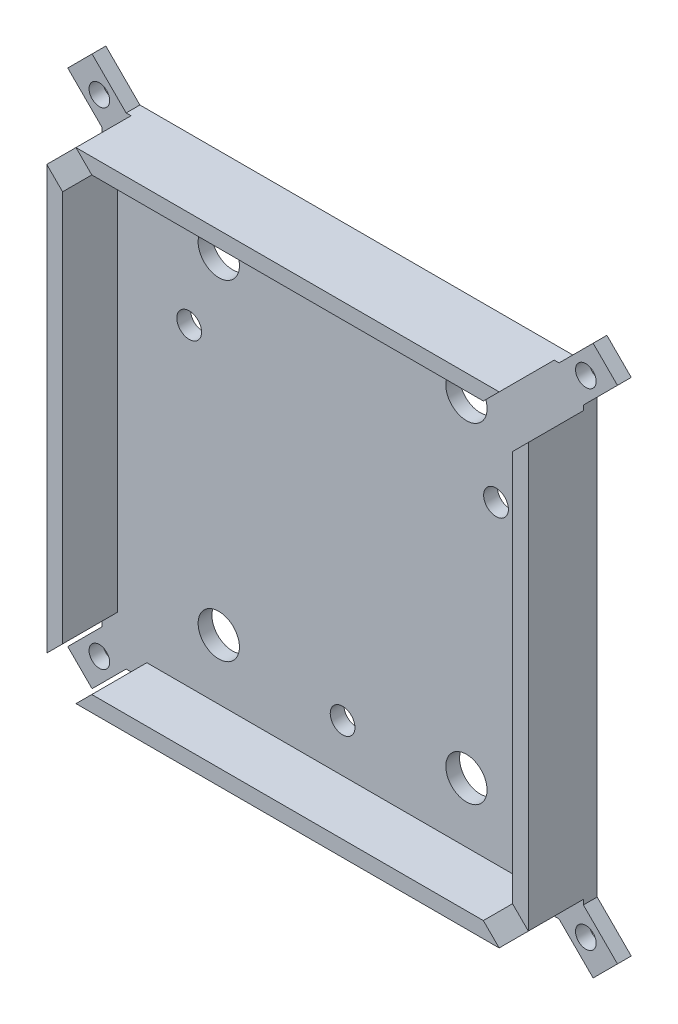
SolidWorks part; units mm, degrees
ref_plane "前视基准面" through (0, 0, 0) normal (0, 0, 1) x (1, 0, 0)
ref_plane "上视基准面" through (0, 0, 0) normal (0, 1, 0) x (1, 0, 0)
ref_plane "右视基准面" through (0, 0, 0) normal (1, 0, 0) x (0, 0, -1)
other "Configuration Table"
sketch "草图1" plane through (0, 0, 0) normal (0, 0, 1) x (1, 0, 0)
  line L1 (-33, -35) -> (33, -35)
  line L2 (-35, -33) -> (-35, 33)
  line L3 (-33, 35) -> (33, 35)
  line L4 (35, -33) -> (35, 33)
  line L5 (-35, -35) -> (35, 35) construction
  line L6 (-35, 35) -> (35, -35) construction
  arc A2 (-33, -35) -> (-35, -33) centre (-33, -33) cw
  arc A3 (33, -35) -> (35, -33) centre (33, -33) ccw
  arc A4 (35, 33) -> (33, 35) centre (33, 33) ccw
  arc A5 (-35, 33) -> (-33, 35) centre (-33, 33) cw
  point P0 (0, 0)
  dimension "D1" = 70
  dimension "D2" = 70
  dimension "D3" = 2
extrude "凸台-拉伸1" add sketch "草图1" along normal blind 10 contours A5 L2 A2 L1 A3 L4 A4 L3
sketch "草图2" plane through (0, 0, 10) normal (0, 0, 1) x (1, 0, 0)
  line L0 (-24, 18) -> (24, 18) construction
  line L1 (24, 18) -> (24, -18) construction
  line L2 (24, -18) -> (-24, -18) construction
  line L3 (-24, -18) -> (-24, 18) construction
  line L4 (-24, 18) -> (24, -18) construction
  line L5 (24, 18) -> (-24, -18) construction
  line L6 (-29.7, -32.7) -> (29.7, -32.7)
  line L7 (-32.7, -29.7) -> (-32.7, 29.7)
  line L8 (-29.7, 32.7) -> (29.7, 32.7)
  line L9 (32.7, -29.7) -> (32.7, 29.7)
  line L10 (-32.7, -32.7) -> (32.7, 32.7) construction
  line L11 (-32.7, 32.7) -> (32.7, -32.7) construction
  circle A0 centre (24, 18) radius 1.8
  circle A1 centre (-24, 18) radius 1.8
  circle A2 centre (-24, -18) radius 1.8
  circle A3 centre (24, -18) radius 1.8
  arc A4 (-32.7, 29.7) -> (-29.7, 32.7) centre (-29.7, 29.7) cw
  arc A5 (-32.7, -29.7) -> (-29.7, -32.7) centre (-29.7, -29.7) ccw
  arc A6 (29.7, -32.7) -> (32.7, -29.7) centre (29.7, -29.7) ccw
  arc A7 (32.7, 29.7) -> (29.7, 32.7) centre (29.7, 29.7) ccw
  point P8 (0, 0)
  point P9 (0, 0)
  dimension "D3" = 3.6
  dimension "D4" = 3.6
  dimension "D5" = 3.6
  dimension "D6" = 3.6
  dimension "D8" = 3
  dimension "D9" = 3
  dimension "D1" = 48
  dimension "D2" = 36
  dimension "D7" = 65.4
extrude "切除-拉伸1" cut sketch "草图2" against normal offset from surface (8 mm away) 2 contours L8 A7 L9 A6 L6 A5 L7 A4 up to face at (0, 0, 0)
sketch "草图3" plane through (0, 0, 0) normal (0, 0, -1) x (-1, 0, 0)
  line L0 (-14.4627, 17.236) -> (-18.6408, 22.2153)
  line L1 (-28.5594, 5.0358) -> (-22.1582, 3.9071)
  line L2 (-25.1147, 14.5) -> (-19.4856, 11.25)
  line L3 (0, 0) -> (50000, 0) construction
  line L4 (0, 0) -> (0, 50000) construction
  line L5 (22.1582, 3.9071) -> (28.5594, 5.0358)
  line L6 (18.6408, 22.2153) -> (14.4627, 17.236)
  line L7 (-7.6955, -21.1431) -> (-9.9186, -27.2511)
  line L8 (9.9186, -27.2511) -> (7.6955, -21.1431)
  arc A0 (-18.6408, 22.2153) -> (-28.5594, 5.0358) centre (0, 0) ccw
  arc A1 (-14.4627, 17.236) -> (-22.1582, 3.9071) centre (0, 0) ccw
  circle A2 centre (0, 0) radius 22.5 construction
  circle A3 centre (0, 0) radius 29 construction
  arc A4 (22.1582, 3.9071) -> (14.4627, 17.236) centre (0, 0) ccw
  arc A5 (28.5594, 5.0358) -> (18.6408, 22.2153) centre (0, 0) ccw
  arc A6 (-7.6955, -21.1431) -> (7.6955, -21.1431) centre (0, 0) ccw
  arc A7 (-9.9186, -27.2511) -> (9.9186, -27.2511) centre (0, 0) ccw
  circle A8 centre (-22.3002, 12.875) radius 1.8
  circle A9 centre (22.3002, 12.875) radius 1.8
  circle A10 centre (0, -25.75) radius 1.8
  point P9 (-22.3002, 12.875)
  point P25 (0, 0)
  point P32 (0, 0)
  dimension "D1" = 45
  dimension "D2" = 58
  dimension "D6" = 3.6
  dimension "D3" = 25.75
  dimension "D4" = 20
  dimension "D5" = 30
extrude "切除-拉伸2" cut sketch "草图3" against normal up to next contours A8 | A9 | A10
sketch "草图4" plane through (0, 0, 0) normal (0, 0, -1) x (-1, 0, 0)
  line L0 (-18, 24) -> (18, 24) construction
  line L1 (18, 24) -> (18, -24) construction
  line L2 (18, -24) -> (-18, -24) construction
  line L3 (-18, -24) -> (-18, 24) construction
  line L4 (-18, 24) -> (18, -24) construction
  line L5 (18, 24) -> (-18, -24) construction
  line L6 (-32.7, -32.7) -> (32.7, -32.7)
  line L7 (-32.7, -32.7) -> (-32.7, 32.7)
  line L8 (-32.7, 32.7) -> (32.7, 32.7)
  line L9 (32.7, -32.7) -> (32.7, 32.7)
  line L10 (-32.7, -32.7) -> (32.7, 32.7) construction
  line L11 (-32.7, 32.7) -> (32.7, -32.7) construction
  circle A0 centre (18, 24) radius 3
  circle A1 centre (-18, 24) radius 3
  circle A2 centre (-18, -24) radius 3
  circle A3 centre (18, -24) radius 3
  point P8 (0, 0)
  point P9 (0, 0)
  dimension "D3" = 6
  dimension "D4" = 6
  dimension "D5" = 6
  dimension "D6" = 6
  dimension "D1" = 36
  dimension "D2" = 48
  dimension "D7" = 65.4
extrude "切除-拉伸3" cut sketch "草图4" against normal through all contours A1 | A0 | A2 | A3
sketch "草图5" plane through (0, 0, 10) normal (0, 0, 1) x (1, 0, 0)
  line L0 (0, 0) -> (-34.4142, 34.4142) construction
  line L1 (-36.182, 32.6464) -> (-32.6464, 36.182) construction
  line L4 (33, 35) -> (-33, 35)
  line L5 (-35, 33) -> (-35, -33)
  line L6 (-33, -35) -> (33, -35)
  line L7 (35, -33) -> (35, 33)
  line L8 (33, 35) -> (-33, 35)
  line L9 (-35, 33) -> (-35, -33)
  line L10 (-33, -35) -> (33, -35)
  line L11 (35, -33) -> (35, 33)
  line L12 (-36.182, 32.6464) -> (-39.9515, 36.416)
  line L13 (-32.6464, 36.182) -> (-36.416, 39.9515)
  line L14 (-39.9515, 36.416) -> (-36.416, 39.9515)
  line L15 (-36.182, 32.6464) -> (-32.6464, 36.182) construction
  line L16 (-36.182, 32.6464) -> (-32.1734, 28.6378)
  line L17 (-32.6464, 36.182) -> (-28.6378, 32.1734)
  line L18 (-32.1734, 28.6378) -> (-28.6378, 32.1734)
  line L19 (32.6464, 36.182) -> (36.416, 39.9515)
  line L20 (36.182, 32.6464) -> (39.9515, 36.416)
  line L21 (36.416, 39.9515) -> (39.9515, 36.416)
  line L22 (32.6464, 36.182) -> (28.6378, 32.1734)
  line L23 (36.182, 32.6464) -> (32.1734, 28.6378)
  line L24 (28.6378, 32.1734) -> (32.1734, 28.6378)
  line L25 (32.6464, 36.182) -> (36.182, 32.6464) construction
  line L26 (32.6464, 36.182) -> (36.182, 32.6464) construction
  line L27 (36.182, -32.6464) -> (39.9515, -36.416)
  line L28 (32.6464, -36.182) -> (36.416, -39.9515)
  line L29 (39.9515, -36.416) -> (36.416, -39.9515)
  line L30 (36.182, -32.6464) -> (32.1734, -28.6378)
  line L31 (32.6464, -36.182) -> (28.6378, -32.1734)
  line L32 (32.1734, -28.6378) -> (28.6378, -32.1734)
  line L33 (36.182, -32.6464) -> (32.6464, -36.182) construction
  line L34 (36.182, -32.6464) -> (32.6464, -36.182) construction
  line L35 (-32.6464, -36.182) -> (-36.416, -39.9515)
  line L36 (-36.182, -32.6464) -> (-39.9515, -36.416)
  line L37 (-36.416, -39.9515) -> (-39.9515, -36.416)
  line L38 (-32.6464, -36.182) -> (-28.6378, -32.1734)
  line L39 (-36.182, -32.6464) -> (-32.1734, -28.6378)
  line L40 (-28.6378, -32.1734) -> (-32.1734, -28.6378)
  line L41 (-32.6464, -36.182) -> (-36.182, -32.6464) construction
  line L42 (-32.6464, -36.182) -> (-36.182, -32.6464) construction
  arc A0 (35, 33) -> (33, 35) centre (33, 33) ccw
  arc A1 (33, -35) -> (35, -33) centre (33, -33) ccw
  arc A2 (-35, -33) -> (-33, -35) centre (-33, -33) ccw
  arc A4 (-33, 35) -> (-35, 33) centre (-33, 33) ccw
  arc A5 (-35, -33) -> (-33, -35) centre (-33, -33) ccw
  arc A6 (33, -35) -> (35, -33) centre (33, -33) ccw
  arc A7 (35, 33) -> (33, 35) centre (33, 33) ccw
  arc A8 (-33, 35) -> (-35, 33) centre (-33, 33) ccw
  arc A9 (-35, -33) -> (-33, -35) centre (-33, -33) ccw
  arc A10 (33, -35) -> (35, -33) centre (33, -33) ccw
  arc A11 (35, 33) -> (33, 35) centre (33, 33) ccw
  point P12 (-34.4142, 34.4142)
  point P52 (0, 0)
  arc M21 (-29.7, -32.7) -> (-32.7, -29.7) centre (-29.7, -29.7) cw
  line M22 (-32.7, -29.7) -> (-32.7, 29.7)
  arc M23 (-32.7, 29.7) -> (-29.7, 32.7) centre (-29.7, 29.7) cw
  line M24 (-29.7, 32.7) -> (29.7, 32.7)
  arc M25 (29.7, 32.7) -> (32.7, 29.7) centre (29.7, 29.7) cw
  line M26 (32.7, 29.7) -> (32.7, -29.7)
  arc M27 (32.7, -29.7) -> (29.7, -32.7) centre (29.7, -29.7) cw
  line M28 (29.7, -32.7) -> (-29.7, -32.7)
  line M29 (33, 35) -> (-33, 35)
  arc M30 (-33, 35) -> (-35, 33) centre (-33, 33) ccw
  line M31 (-35, 33) -> (-35, -33)
  arc M32 (-35, -33) -> (-33, -35) centre (-33, -33) ccw
  line M33 (-33, -35) -> (33, -35)
  arc M34 (33, -35) -> (35, -33) centre (33, -33) ccw
  line M35 (35, -33) -> (35, 33)
  arc M36 (35, 33) -> (33, 35) centre (33, 33) ccw
  dimension "D2" = 4
  dimension "D3" = 5
  dimension "D4" = 43
  dimension "D5" = 54
  dimension "D1" = 0
extrude "凸台-拉伸2" add sketch "草图5" against normal up to surface (10 mm away) contours L17 L8 L16 M30 M31 M22 M23 M24 | L17 L13 L14 L12 L16 L8 M31 M30 | L23 L11 L22 M36 M29 M24 M25 M26 | L23 L20 L21 L19 L22 L11 M29 M36 | L31 L28 L29 L27 L30 L10 M35 M34 | L31 L10 L30 M34 M35 M26 M27 M28 | L39 L36 L37 L35 L38 M33 M32 M31 | L39 L38 M31 M32 M33 M28 M21 M22 up to face at (-21, 24, 0)
sketch "草图6" plane through (0, 0, 10) normal (0, 0, 1) x (1, 0, 0)
  line L0 (32.5, -32.5) -> (32.5, 32.5) construction
  line L1 (32.5, 32.5) -> (-32.5, 32.5) construction
  line L2 (-32.5, -32.5) -> (32.5, -32.5) construction
  line L3 (0, 0) -> (-38.1838, 38.1838) construction
  line L13 (-28.2574, -32.5) -> (28.2574, -32.5)
  line L16 (-36.416, -39.9515) -> (-31.4645, -35)
  line L17 (-31.4645, -35) -> (31.4645, -35)
  line L18 (31.4645, -35) -> (36.416, -39.9515)
  line L19 (36.416, -39.9515) -> (39.9515, -36.416)
  line L20 (39.9515, -36.416) -> (35, -31.4645)
  line L21 (35, -31.4645) -> (35, 31.4645)
  line L22 (35, 31.4645) -> (39.9515, 36.416)
  line L23 (39.9515, 36.416) -> (36.416, 39.9515)
  line L24 (36.416, 39.9515) -> (31.4645, 35)
  line L25 (31.4645, 35) -> (-31.4645, 35)
  line L26 (-31.4645, 35) -> (-36.416, 39.9515)
  line L27 (-36.416, 39.9515) -> (-39.9515, 36.416)
  line L28 (-39.9515, 36.416) -> (-35, 31.4645)
  line L29 (-35, 31.4645) -> (-35, -31.4645)
  line L30 (-35, -31.4645) -> (-39.9515, -36.416)
  line L31 (-39.9515, -36.416) -> (-36.416, -39.9515)
  line L32 (-36.416, -39.9515) -> (-31.4645, -35)
  line L33 (-31.4645, -35) -> (31.4645, -35)
  line L34 (31.4645, -35) -> (36.416, -39.9515)
  line L35 (36.416, -39.9515) -> (39.9515, -36.416)
  line L36 (39.9515, -36.416) -> (35, -31.4645)
  line L37 (35, -31.4645) -> (35, 31.4645)
  line L38 (35, 31.4645) -> (39.9515, 36.416)
  line L39 (39.9515, 36.416) -> (36.416, 39.9515)
  line L40 (36.416, 39.9515) -> (31.4645, 35)
  line L41 (31.4645, 35) -> (-31.4645, 35)
  line L42 (-31.4645, 35) -> (-36.416, 39.9515)
  line L43 (-36.416, 39.9515) -> (-39.9515, 36.416)
  line L44 (-39.9515, 36.416) -> (-35, 31.4645)
  line L45 (-35, 31.4645) -> (-35, -31.4645)
  line L46 (-35, -31.4645) -> (-39.9515, -36.416)
  line L47 (-39.9515, -36.416) -> (-36.416, -39.9515)
  line L49 (32.5, -28.2574) -> (32.5, 28.2574)
  line L53 (28.2574, 32.5) -> (-28.2574, 32.5)
  line L57 (-32.5, 28.2574) -> (-32.5, -28.2574)
  line L61 (-35, 30.7574) -> (-31.8859, 27.6432)
  line L62 (-31.8859, 27.6432) -> (-27.6432, 31.8859)
  line L63 (-27.6432, 31.8859) -> (-30.7574, 35)
  line L66 (27.6432, 31.8859) -> (31.8859, 27.6432)
  line L67 (31.8859, 27.6432) -> (35, 30.7574)
  line L68 (30.7574, 35) -> (27.6432, 31.8859)
  line L69 (31.8859, -27.6432) -> (27.6432, -31.8859)
  line L70 (27.6432, -31.8859) -> (30.7574, -35)
  line L71 (35, -30.7574) -> (31.8859, -27.6432)
  line L72 (-27.6432, -31.8859) -> (-31.8859, -27.6432)
  line L73 (-31.8859, -27.6432) -> (-35, -30.7574)
  line L74 (-30.7574, -35) -> (-27.6432, -31.8859)
  line L76 (-32.5, 32.5) -> (-32.5, -32.5) construction
  line L78 (-32.5, 32.5) -> (-36.416, 36.416) construction
  line L79 (-36.416, 36.416) -> (-32.5, 32.5) construction
  line L80 (32.5, 32.5) -> (36.416, 36.416) construction
  line L81 (36.416, 36.416) -> (32.5, 32.5) construction
  line L82 (36.416, -36.416) -> (32.5, -32.5) construction
  line L83 (32.5, -32.5) -> (36.416, -36.416) construction
  line L84 (-36.416, -36.416) -> (-32.5, -32.5) construction
  line L85 (-32.5, -32.5) -> (-36.416, -36.416) construction
  line L88 (-36.416, 36.416) -> (-36.416, 36.416) construction
  line L89 (36.416, 36.416) -> (36.416, 36.416) construction
  line L90 (36.416, -36.416) -> (36.416, -36.416) construction
  line L91 (-36.416, -36.416) -> (-36.416, -36.416) construction
  point P33 (0, 0)
  point P70 (0, 0)
  line M23 (-36.416, -39.9515) -> (-31.4645, -35)
  line M24 (-31.4645, -35) -> (31.4645, -35)
  line M25 (31.4645, -35) -> (36.416, -39.9515)
  line M26 (36.416, -39.9515) -> (39.9515, -36.416)
  line M27 (39.9515, -36.416) -> (35, -31.4645)
  line M28 (35, -31.4645) -> (35, 31.4645)
  line M29 (35, 31.4645) -> (39.9515, 36.416)
  line M30 (39.9515, 36.416) -> (36.416, 39.9515)
  line M31 (36.416, 39.9515) -> (31.4645, 35)
  line M32 (31.4645, 35) -> (-31.4645, 35)
  line M33 (-31.4645, 35) -> (-36.416, 39.9515)
  line M34 (-36.416, 39.9515) -> (-39.9515, 36.416)
  line M35 (-39.9515, 36.416) -> (-35, 31.4645)
  line M36 (-35, 31.4645) -> (-35, -31.4645)
  line M37 (-35, -31.4645) -> (-39.9515, -36.416)
  line M38 (-39.9515, -36.416) -> (-36.416, -39.9515)
  arc M39 (32.7, -29.7) -> (29.7, -32.7) centre (29.7, -29.7) cw
  line M40 (29.7, -32.7) -> (-29.7, -32.7)
  arc M41 (-29.7, -32.7) -> (-32.7, -29.7) centre (-29.7, -29.7) cw
  line M42 (-32.7, -29.7) -> (-32.7, 29.7)
  arc M43 (-32.7, 29.7) -> (-29.7, 32.7) centre (-29.7, 29.7) cw
  line M44 (-29.7, 32.7) -> (29.7, 32.7)
  arc M45 (29.7, 32.7) -> (32.7, 29.7) centre (29.7, 29.7) cw
  line M46 (32.7, 29.7) -> (32.7, -29.7)
  dimension "D2" = 54
  dimension "D1" = 0
  dimension "D3" = 2.5
extrude "切除-拉伸4" cut sketch "草图6" against normal offset from surface (8 mm away) 2 contours L74 L73 M24 M40 M41 M42 M36 M37 M38 M23 | L74 L72 L73 M40 M42 M41 | L71 L70 L33 M28 M46 M39 M40 M25 M26 M27 | L71 L69 L70 M46 M40 M39 | L68 L67 L37 M32 M44 M45 M46 M29 M30 M31 | L68 L66 L67 M44 M46 M45 | L62 L63 L61 M44 M43 M42 | L63 L41 L61 M44 M33 M34 M35 M36 M42 M43 up to face at (0, 0, 0)
sketch "草图7" plane through (0, 0, 2) normal (0, 0, 1) x (1, 0, 0)
  line L0 (0, 0) -> (-38.1838, 38.1838) construction
  line L32 (-35, 30.7574) -> (-32.7, 28.4574)
  line L33 (-32.7, 28.4574) -> (-32.7, -28.4574)
  line L34 (-32.7, -28.4574) -> (-35, -30.7574)
  line L35 (-35, -30.7574) -> (-35, -31.4645)
  line L36 (-35, -31.4645) -> (-39.9515, -36.416)
  line L37 (-39.9515, -36.416) -> (-36.416, -39.9515)
  line L38 (-36.416, -39.9515) -> (-31.4645, -35)
  line L39 (-31.4645, -35) -> (-30.7574, -35)
  line L40 (-30.7574, -35) -> (-28.4574, -32.7)
  line L41 (-28.4574, -32.7) -> (28.4574, -32.7)
  line L42 (28.4574, -32.7) -> (30.7574, -35)
  line L43 (30.7574, -35) -> (31.4645, -35)
  line L44 (31.4645, -35) -> (36.416, -39.9515)
  line L45 (36.416, -39.9515) -> (39.9515, -36.416)
  line L46 (39.9515, -36.416) -> (35, -31.4645)
  line L47 (35, -31.4645) -> (35, -30.7574)
  line L48 (35, -30.7574) -> (32.7, -28.4574)
  line L49 (32.7, -28.4574) -> (32.7, 28.4574)
  line L50 (32.7, 28.4574) -> (35, 30.7574)
  line L51 (35, 30.7574) -> (35, 31.4645)
  line L52 (35, 31.4645) -> (39.9515, 36.416)
  line L53 (39.9515, 36.416) -> (36.416, 39.9515)
  line L54 (36.416, 39.9515) -> (31.4645, 35)
  line L55 (31.4645, 35) -> (30.7574, 35)
  line L56 (30.7574, 35) -> (28.4574, 32.7)
  line L57 (28.4574, 32.7) -> (-28.4574, 32.7)
  line L58 (-28.4574, 32.7) -> (-30.7574, 35)
  line L59 (-30.7574, 35) -> (-31.4645, 35)
  line L60 (-31.4645, 35) -> (-36.416, 39.9515)
  line L61 (-36.416, 39.9515) -> (-39.9515, 36.416)
  line L62 (-39.9515, 36.416) -> (-35, 31.4645)
  line L63 (-35, 31.4645) -> (-35, 30.7574)
  line L64 (-35, 30.7574) -> (-32.7, 28.4574)
  line L65 (-32.7, 28.4574) -> (-32.7, -28.4574)
  line L66 (-32.7, -28.4574) -> (-35, -30.7574)
  line L67 (-35, -30.7574) -> (-35, -31.4645)
  line L68 (-35, -31.4645) -> (-39.9515, -36.416)
  line L69 (-39.9515, -36.416) -> (-36.416, -39.9515)
  line L70 (-36.416, -39.9515) -> (-31.4645, -35)
  line L71 (-31.4645, -35) -> (-30.7574, -35)
  line L72 (-30.7574, -35) -> (-28.4574, -32.7)
  line L73 (-28.4574, -32.7) -> (28.4574, -32.7)
  line L74 (28.4574, -32.7) -> (30.7574, -35)
  line L75 (30.7574, -35) -> (31.4645, -35)
  line L76 (31.4645, -35) -> (36.416, -39.9515)
  line L77 (36.416, -39.9515) -> (39.9515, -36.416)
  line L78 (39.9515, -36.416) -> (35, -31.4645)
  line L79 (35, -31.4645) -> (35, -30.7574)
  line L80 (35, -30.7574) -> (32.7, -28.4574)
  line L81 (32.7, -28.4574) -> (32.7, 28.4574)
  line L82 (32.7, 28.4574) -> (35, 30.7574)
  line L83 (35, 30.7574) -> (35, 31.4645)
  line L84 (35, 31.4645) -> (39.9515, 36.416)
  line L85 (39.9515, 36.416) -> (36.416, 39.9515)
  line L86 (36.416, 39.9515) -> (31.4645, 35)
  line L87 (31.4645, 35) -> (30.7574, 35)
  line L88 (30.7574, 35) -> (28.4574, 32.7)
  line L89 (28.4574, 32.7) -> (-28.4574, 32.7)
  line L90 (-28.4574, 32.7) -> (-30.7574, 35)
  line L91 (-30.7574, 35) -> (-31.4645, 35)
  line L92 (-31.4645, 35) -> (-36.416, 39.9515)
  line L93 (-36.416, 39.9515) -> (-39.9515, 36.416)
  line L94 (-39.9515, 36.416) -> (-35, 31.4645)
  line L95 (-35, 31.4645) -> (-35, 30.7574)
  circle A0 centre (-35.3553, 35.3553) radius 1.5
  circle A1 centre (35.3553, 35.3553) radius 1.5
  circle A2 centre (35.3553, -35.3553) radius 1.5
  circle A3 centre (-35.3553, -35.3553) radius 1.5
  point P28 (0, 0)
  dimension "D4" = 3
  dimension "D2" = 50
  dimension "D1" = 0
  dimension "D3" = 4
extrude "切除-拉伸5" cut sketch "草图7" against normal up to next contours L0 A0 | A0 L0 | A1 | A2 | A3
